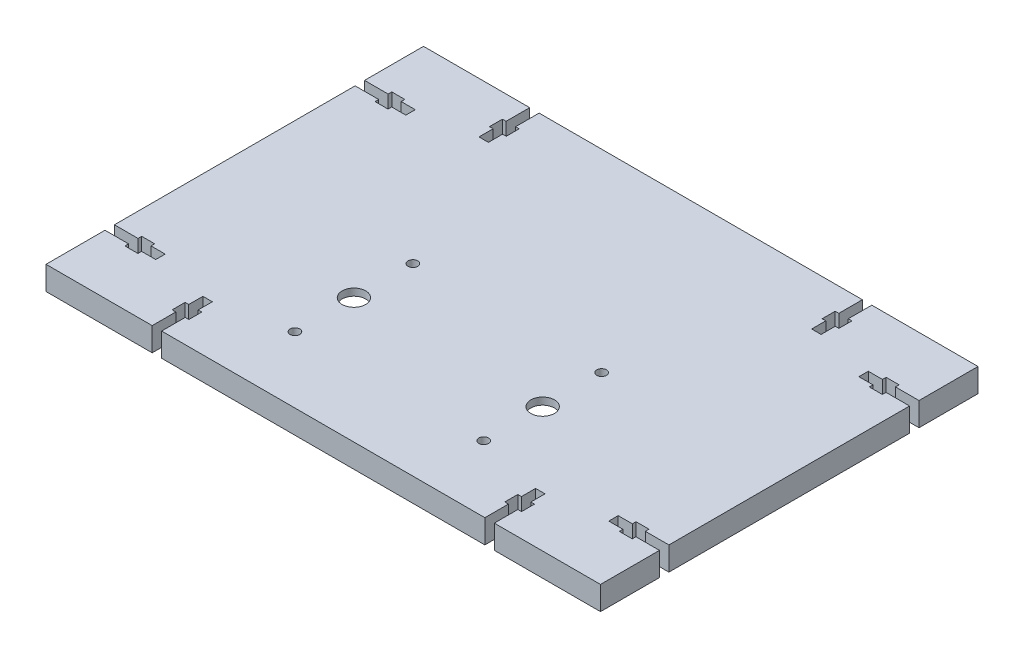
SolidWorks part; units mm, degrees
ref_plane "Front Plane" through (0, 0, 0) normal (0, 0, 1) x (1, 0, 0)
ref_plane "Top Plane" through (0, 0, 0) normal (0, 1, 0) x (1, 0, 0)
ref_plane "Right Plane" through (0, 0, 0) normal (1, 0, 0) x (0, 0, -1)
sketch "Sketch1" plane through (0, 0, 0) normal (0, 0, 1) x (1, 0, 0)
  line L1 (0, 0) -> (235, 0)
  line L2 (0, 0) -> (0, 10)
  line L3 (0, 10) -> (235, 10)
  line L4 (235, 0) -> (235, 10)
  dimension "D1" = 10
  dimension "D2" = 235
extrude "Boss-Extrude1" add sketch "Sketch1" along normal blind 160
sketch "Sketch3" plane through (0, 0, 0) normal (0, -1, 0) x (1, 0, 0)
  line L0 (117.5, 160) -> (117.5, 0) construction
  line L1 (0, 160) -> (235, 160) construction
  line L2 (0, 0) -> (235, 0) construction
  line L3 (117.5, 107) -> (137.5, 107) construction
  line L4 (137.5, 132) -> (137.5, 82)
  line L5 (177.5, 132) -> (177.5, 82)
  line L6 (137.5, 107) -> (177.5, 107) construction
  line L7 (57.5, 132) -> (57.5, 82)
  line L8 (97.5, 132) -> (97.5, 82)
  arc A0 (137.5, 132) -> (177.5, 132) centre (157.5, 132) cw
  arc A1 (177.5, 82) -> (137.5, 82) centre (157.5, 82) cw
  arc A2 (97.5, 132) -> (57.5, 132) centre (77.5, 132) ccw
  arc A3 (57.5, 82) -> (97.5, 82) centre (77.5, 82) ccw
  point P10 (137.5, 107)
  dimension "D1" = 107
  dimension "D2" = 20
  dimension "D3" = 50
  dimension "D4" = 40
  dimension "D5" = 50
extrude "Cut-Extrude1" cut sketch "Sketch3" against normal blind 7
sketch "Sketch5" plane through (0, 7, 0) normal (0, -1, 0) x (1, 0, 0)
  line L0 (0, 0) -> (235, 0) construction
  line L1 (57.5, 132) -> (57.5, 82) construction
  line L2 (117.5, 0) -> (117.5, 160) construction
  line L3 (0, 160) -> (235, 160) construction
  circle A0 centre (77.5, 107) radius 5
  circle A1 centre (157.5, 107) radius 5
  dimension "D1" = 107
  dimension "D2" = 20
  dimension "D3" = 10
extrude "Cut-Extrude2" cut sketch "Sketch5" against normal blind 33
sketch "Sketch6" plane through (0, 7, 0) normal (0, -1, 0) x (1, 0, 0)
  line L0 (57.5, 132) -> (57.5, 82) construction
  line L1 (57.5, 107) -> (207.409, 107) construction
  line L2 (117.5, 0) -> (117.5, 160) construction
  line L3 (0, 0) -> (235, 0) construction
  line L4 (0, 160) -> (235, 160) construction
  line L6 (97.5, 82) -> (97.5, 132) construction
  circle A0 centre (77.5, 82) radius 2.05
  circle A2 centre (77.5, 132) radius 2.05
  circle A3 centre (157.5, 82) radius 2.05
  circle A4 centre (157.5, 132) radius 2.05
  arc A6 (97.5, 132) -> (57.5, 132) centre (77.5, 132) ccw construction
  dimension "D1" = 20
  dimension "D2" = 50
  dimension "D3" = 4.1
extrude "Cut-Extrude3" cut sketch "Sketch6" against normal blind 33
sketch "Esquisse2" plane through (0, 0, 0) normal (0, -1, 0) x (1, 0, 0)
  line L1 (0, 160) -> (235, 160) construction
  line L13 (0, 135) -> (10, 135)
  line L14 (0, 160) -> (0, 0) construction
  line L15 (10, 135) -> (10, 136.55)
  line L16 (10, 136.55) -> (15.5, 136.55)
  line L17 (15.5, 136.55) -> (15.5, 135)
  line L18 (15.5, 135) -> (21.5, 135)
  line L19 (21.5, 135) -> (21.5, 131)
  line L20 (0, 135) -> (0, 131)
  line L21 (0, 133) -> (21.5, 133) construction
  line L22 (15.5, 131) -> (21.5, 131)
  line L23 (15.5, 129.45) -> (15.5, 131)
  line L24 (10, 129.45) -> (15.5, 129.45)
  line L25 (10, 131) -> (10, 129.45)
  line L26 (0, 131) -> (10, 131)
  line L27 (0, 80) -> (36.9012, 80) construction
  line L28 (117.5, 0) -> (117.5, 24.5762) construction
  line L29 (0, 0) -> (235, 0) construction
  line L30 (235, 80) -> (208.9845, 80) construction
  line L31 (235, 160) -> (235, 0) construction
  line L32 (117.5, 160) -> (117.5, 141) construction
  line L33 (0, 27) -> (21.5, 27) construction
  line L34 (0, 29) -> (10, 29)
  line L35 (10, 29) -> (10, 30.55)
  line L36 (10, 30.55) -> (15.5, 30.55)
  line L37 (15.5, 30.55) -> (15.5, 29)
  line L38 (15.5, 29) -> (21.5, 29)
  line L39 (0, 25) -> (0, 29)
  line L40 (21.5, 25) -> (21.5, 29)
  line L41 (15.5, 25) -> (21.5, 25)
  line L42 (15.5, 23.45) -> (15.5, 25)
  line L43 (10, 23.45) -> (15.5, 23.45)
  line L44 (10, 25) -> (10, 23.45)
  line L45 (0, 25) -> (10, 25)
  line L46 (235, 27) -> (213.5, 27) construction
  line L47 (235, 80) -> (198.0988, 80) construction
  line L48 (235, 133) -> (213.5, 133) construction
  line L49 (235, 25) -> (225, 25)
  line L50 (225, 25) -> (225, 23.45)
  line L51 (225, 23.45) -> (219.5, 23.45)
  line L52 (219.5, 23.45) -> (219.5, 25)
  line L53 (219.5, 25) -> (213.5, 25)
  line L54 (213.5, 25) -> (213.5, 29)
  line L55 (235, 25) -> (235, 29)
  line L56 (219.5, 29) -> (213.5, 29)
  line L57 (219.5, 30.55) -> (219.5, 29)
  line L58 (225, 30.55) -> (219.5, 30.55)
  line L59 (225, 29) -> (225, 30.55)
  line L60 (235, 29) -> (225, 29)
  line L61 (235, 131) -> (225, 131)
  line L62 (225, 131) -> (225, 129.45)
  line L63 (225, 129.45) -> (219.5, 129.45)
  line L64 (219.5, 129.45) -> (219.5, 131)
  line L65 (219.5, 131) -> (213.5, 131)
  line L66 (235, 135) -> (235, 131)
  line L67 (213.5, 135) -> (213.5, 131)
  line L68 (219.5, 135) -> (213.5, 135)
  line L69 (219.5, 136.55) -> (219.5, 135)
  line L70 (225, 136.55) -> (219.5, 136.55)
  line L71 (225, 135) -> (225, 136.55)
  line L72 (235, 135) -> (225, 135)
  dimension "D1" = 4
  dimension "D2" = 5.5
  dimension "D3" = 7.1
  dimension "D4" = 4
  dimension "D5" = 6
  dimension "D6" = 10
  dimension "D7" = 25
extrude "Enlèv. mat.-Extru.2" cut sketch "Esquisse2" against normal blind 10
sketch "Esquisse3" plane through (0, 0, 0) normal (0, -1, 0) x (1, 0, 0)
  line L0 (45, 160) -> (45, 150)
  line L1 (0, 160) -> (235, 160) construction
  line L2 (45, 150) -> (43.45, 150)
  line L3 (43.45, 150) -> (43.45, 144.5)
  line L4 (43.45, 144.5) -> (45, 144.5)
  line L5 (45, 144.5) -> (45, 138.5)
  line L6 (45, 138.5) -> (49, 138.5)
  line L7 (47, 138.5) -> (47, 160) construction
  line L8 (45, 160) -> (49, 160)
  line L9 (49, 144.5) -> (49, 138.5)
  line L10 (50.55, 144.5) -> (49, 144.5)
  line L11 (50.55, 150) -> (50.55, 144.5)
  line L12 (49, 150) -> (50.55, 150)
  line L13 (49, 160) -> (49, 150)
  line L14 (0, 160) -> (0, 135) construction
  line L16 (0, 80) -> (235, 80) construction
  line L17 (0, 131) -> (0, 29) construction
  line L18 (235, 131) -> (235, 29) construction
  line L19 (117.5, 160) -> (117.5, 0) construction
  line L20 (0, 0) -> (235, 0) construction
  line L21 (45, 160) -> (45, 150)
  line L22 (45, 150) -> (43.45, 150)
  line L23 (43.45, 150) -> (43.45, 144.5)
  line L24 (43.45, 144.5) -> (45, 144.5)
  line L25 (45, 144.5) -> (45, 138.5)
  line L26 (49, 144.5) -> (49, 138.5)
  line L27 (50.55, 144.5) -> (49, 144.5)
  line L28 (50.55, 150) -> (50.55, 144.5)
  line L29 (49, 150) -> (50.55, 150)
  line L30 (49, 160) -> (49, 150)
  line L31 (188, 138.5) -> (188, 160) construction
  line L32 (186, 160) -> (186, 150)
  line L33 (186, 150) -> (184.45, 150)
  line L34 (184.45, 150) -> (184.45, 144.5)
  line L35 (184.45, 144.5) -> (186, 144.5)
  line L36 (186, 144.5) -> (186, 138.5)
  line L37 (190, 144.5) -> (190, 138.5)
  line L38 (191.55, 144.5) -> (190, 144.5)
  line L39 (191.55, 150) -> (191.55, 144.5)
  line L40 (190, 150) -> (191.55, 150)
  line L41 (190, 160) -> (190, 150)
  line L42 (186, 160) -> (186, 150)
  line L43 (186, 150) -> (184.45, 150)
  line L44 (184.45, 150) -> (184.45, 144.5)
  line L45 (184.45, 144.5) -> (186, 144.5)
  line L46 (186, 144.5) -> (186, 138.5)
  line L47 (190, 160) -> (186, 160)
  line L48 (190, 138.5) -> (186, 138.5)
  line L49 (190, 144.5) -> (190, 138.5)
  line L50 (191.55, 144.5) -> (190, 144.5)
  line L51 (191.55, 150) -> (191.55, 144.5)
  line L52 (190, 150) -> (191.55, 150)
  line L53 (190, 160) -> (190, 150)
  line L54 (188, 21.5) -> (188, 0) construction
  line L55 (47, 21.5) -> (47, 0) construction
  line L56 (190, 0) -> (190, 10)
  line L57 (190, 10) -> (191.55, 10)
  line L58 (191.55, 10) -> (191.55, 15.5)
  line L59 (191.55, 15.5) -> (190, 15.5)
  line L60 (190, 15.5) -> (190, 21.5)
  line L61 (190, 21.5) -> (186, 21.5)
  line L62 (190, 0) -> (186, 0)
  line L63 (186, 15.5) -> (186, 21.5)
  line L64 (184.45, 15.5) -> (186, 15.5)
  line L65 (184.45, 10) -> (184.45, 15.5)
  line L66 (186, 10) -> (184.45, 10)
  line L67 (186, 0) -> (186, 10)
  line L68 (190, 0) -> (190, 10)
  line L69 (190, 10) -> (191.55, 10)
  line L70 (191.55, 10) -> (191.55, 15.5)
  line L71 (191.55, 15.5) -> (190, 15.5)
  line L72 (190, 15.5) -> (190, 21.5)
  line L73 (186, 15.5) -> (186, 21.5)
  line L74 (184.45, 15.5) -> (186, 15.5)
  line L75 (184.45, 10) -> (184.45, 15.5)
  line L76 (186, 10) -> (184.45, 10)
  line L77 (186, 0) -> (186, 10)
  line L78 (49, 0) -> (49, 10)
  line L79 (49, 10) -> (50.55, 10)
  line L80 (50.55, 10) -> (50.55, 15.5)
  line L81 (50.55, 15.5) -> (49, 15.5)
  line L82 (49, 15.5) -> (49, 21.5)
  line L83 (45, 15.5) -> (45, 21.5)
  line L84 (43.45, 15.5) -> (45, 15.5)
  line L85 (43.45, 10) -> (43.45, 15.5)
  line L86 (45, 10) -> (43.45, 10)
  line L87 (45, 0) -> (45, 10)
  line L88 (49, 0) -> (49, 10)
  line L89 (49, 10) -> (50.55, 10)
  line L90 (50.55, 10) -> (50.55, 15.5)
  line L91 (50.55, 15.5) -> (49, 15.5)
  line L92 (49, 15.5) -> (49, 21.5)
  line L93 (45, 0) -> (49, 0)
  line L94 (45, 21.5) -> (49, 21.5)
  line L95 (45, 15.5) -> (45, 21.5)
  line L96 (43.45, 15.5) -> (45, 15.5)
  line L97 (43.45, 10) -> (43.45, 15.5)
  line L98 (45, 10) -> (43.45, 10)
  line L99 (45, 0) -> (45, 10)
  dimension "D1" = 2
  dimension "D2" = 2
  dimension "D3" = 10
  dimension "D4" = 6
  dimension "D5" = 5.5
  dimension "D6" = 45
  dimension "D7" = 7.1
extrude "Enlèv. mat.-Extru.3" cut sketch "Esquisse3" against normal blind 10 contours L13 L8 L0 L2 L3 L4 L5 L6 L9 L10 L11 L12 | L48 L37 L38 L39 L40 L41 L47 L32 L33 L34 L35 L36 | L67 L62 L56 L57 L58 L59 L60 L61 L63 L64 L65 L66 | L94 L83 L84 L85 L86 L87 L93 L78 L79 L80 L81 L82
